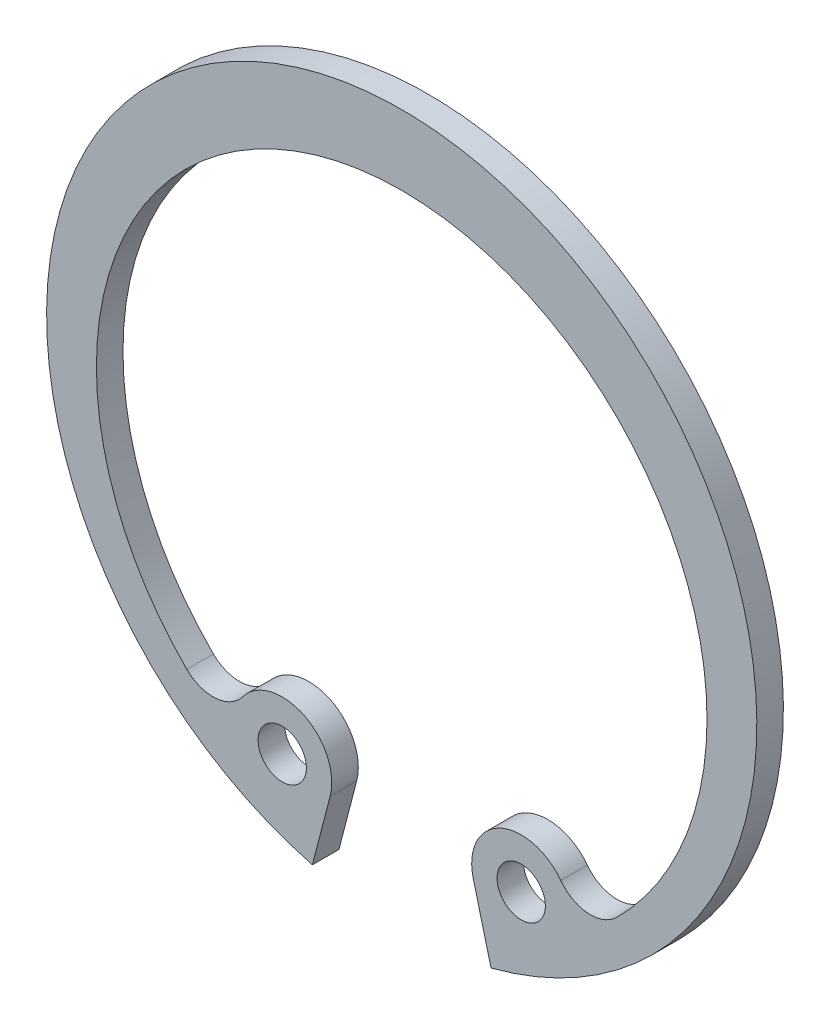
SolidWorks part; units mm, degrees
extrude "Body" add sketch "BodySke" against normal blind 1.1
sketch "BodySke" plane through (0, 0, 0) normal (0, 0, 1) x (1, 0, 0)
  line L0 (-1.5431, 0) -> (1.5431, 0) construction
  line L1 (0, 0) -> (0, 11.8) construction
  line L2 (3.6983, -14.2272) -> (2.9619, -11.3942)
  line L3 (-3.6983, -14.2272) -> (-2.9619, -11.3942)
  line L4 (0, 0) -> (9.8081, -10.9494) construction
  line L5 (0, 0) -> (-9.8081, -10.9494) construction
  line L6 (-4.6944, -9.9106) -> (-5.1975, -11.8463) construction
  line L7 (4.7571, -10.152) -> (5.1348, -11.6049) construction
  arc A0 (-2.9619, -11.3942) -> (-6.5847, -9.6467) centre (-4.946, -10.8784) ccw
  arc A1 (6.5847, -9.6467) -> (2.9619, -11.3942) centre (4.946, -10.8784) ccw
  arc A2 (8.8407, -9.8694) -> (-8.8407, -9.8694) centre (0, -0.8381) ccw construction
  arc A3 (3.6983, -14.2272) -> (-3.6983, -14.2272) centre (0, 0) ccw
  circle A4 centre (4.946, -10.8784) radius 1
  circle A5 centre (-4.946, -10.8784) radius 1
  circle A6 centre (4.946, -10.8784) radius 2.05 construction
  arc A7 (8.8959, -9.815) -> (-8.8959, -9.815) centre (0, -0.8381) ccw
  arc A8 (-4.946, -10.8784) -> (4.946, -10.8784) centre (0, 0) ccw construction
  arc A9 (-8.8959, -9.815) -> (-6.5847, -9.6467) centre (-7.8137, -8.7229) ccw
  arc A10 (6.5847, -9.6467) -> (8.8959, -9.815) centre (7.8137, -8.7229) ccw
  dimension "HoleDia" = 2
  dimension "HoleOffsetRad" = 11.95
  dimension "GrooveDia" = 29.4
  dimension "TipRad" = 2.05
  dimension "FilletRad" = 1.5375
  dimension "LargeRad" = 11.8
  dimension "SmallRad" = 13.25
  dimension "SmallAngle" = 83.706
  dimension "GapAngle" = 29.143
ref_plane "Plane1" through (0, 0, 0) normal (0, 0, 1) x (1, 0, 0)
ref_plane "Plane2" through (0, 0, 0) normal (0, 1, 0) x (1, 0, 0)
ref_plane "Plane3" through (0, 0, 0) normal (1, 0, 0) x (0, 0, -1)
sketch "Clipboard" plane through (0, 0, 0) normal (0, 0, 1) x (1, 0, 0)
  line L0 (0, 0) -> (2.9, 0)
  line L1 (0, 0) -> (0, 1.45)
  line L2 (0, 0) -> (0, -4.8)
  circle A0 centre (0, 0) radius 1
  circle A1 centre (0, 0) radius 14
  dimension "HoleDia" = 2
  dimension "BoreDia" = 28
  dimension "LargeSection" = 2.9
  dimension "SmallSection" = 1.45
  dimension "LugSection" = 4.8
sketch "ModLugSke" plane through (0, 0, 0) normal (0, 0, 1) x (1, 0, 0)
  line L0 (3.6983, -14.2272) -> (2.5157, -9.6779)
  line L1 (-3.6983, -14.2272) -> (-2.5157, -9.6779)
  line L2 (7.9458, -5.9054) -> (11.7983, -8.7687) construction
  line L3 (-7.9458, -5.9054) -> (-11.7983, -8.7687) construction
  line L4 (-3.6983, -14.2272) -> (-2.9619, -11.3942) construction
  line L5 (2.9619, -11.3942) -> (3.6983, -14.2272) construction
  line L6 (0, 0) -> (0, -18.0732) construction
  line L7 (10.5254, -7.8226) -> (11.7983, -8.7687)
  line L8 (-11.7983, -8.7687) -> (-10.5254, -7.8226)
  arc A0 (3.6983, -14.2272) -> (11.7983, -8.7687) centre (0, 0) ccw
  arc A1 (-5.5669, -8.1866) -> (-2.5864, -9.5562) centre (0, 0) ccw
  arc A2 (3.6983, -14.2272) -> (-3.6983, -14.2272) centre (0, 0) ccw construction
  arc A3 (6.5847, -9.6467) -> (2.9619, -11.3942) centre (4.946, -10.8784) ccw construction
  arc A4 (-5.5669, -8.1866) -> (-5.6932, -8.1979) centre (-5.6231, -8.2693) ccw
  arc A5 (-10.5254, -7.8226) -> (-5.6932, -8.1979) centre (-7.9458, -5.9054) ccw
  arc A6 (8.8959, -9.815) -> (-8.8959, -9.815) centre (0, -0.8381) ccw construction
  arc A7 (5.6932, -8.1979) -> (10.5254, -7.8226) centre (7.9458, -5.9054) ccw
  arc A8 (2.5864, -9.5562) -> (5.5669, -8.1866) centre (0, 0) ccw
  arc A9 (-11.7983, -8.7687) -> (-3.6983, -14.2272) centre (0, 0) ccw
  circle A10 centre (-4.946, -10.8784) radius 1
  circle A11 centre (-4.946, -10.8784) radius 1 construction
  circle A12 centre (4.946, -10.8784) radius 1
  circle A13 centre (4.946, -10.8784) radius 1 construction
  arc A14 (-2.5864, -9.5562) -> (-2.5157, -9.6779) centre (-2.6125, -9.6527) cw
  arc A15 (2.5864, -9.5562) -> (2.5157, -9.6779) centre (2.6125, -9.6527) ccw
  arc A16 (5.5669, -8.1866) -> (5.6932, -8.1979) centre (5.6231, -8.2693) cw
  point P43 (2.4907, -9.5816)
  dimension "D1" = 0.1
extrude "ModLug" [suppressed] add sketch "ModLugSke" against normal through all
sketch "UnlSke" [suppressed] plane through (0, 0, 0) normal (0, 0, 1) x (1, 0, 0)
  line L0 (2.1178, -8.3352) -> (3.2259, -12.6966)
  line L1 (-2.1178, -8.3352) -> (-3.2259, -12.6966)
  line L2 (-3.2259, -12.6966) -> (-2.1422, -8.4315) construction
  line L3 (2.1422, -8.4315) -> (3.2259, -12.6966) construction
  arc A0 (2.1178, -8.3352) -> (-2.1178, -8.3352) centre (0, 0) ccw
  arc A1 (3.2259, -12.6966) -> (-3.2259, -12.6966) centre (0, 0) ccw
  arc A2 (3.2259, -12.6966) -> (-3.2259, -12.6966) centre (0, 0) ccw construction
  circle A4 centre (-4.4431, -9.5688) radius 1
  circle A5 centre (4.4431, -9.5688) radius 1
  circle A6 centre (4.4431, -9.5688) radius 1 construction
  circle A7 centre (-4.4431, -9.5688) radius 1 construction
  arc A8 (2.2134, -8.3103) -> (4.9183, -7.0548) centre (0, 0) ccw construction
extrude "Unlug" [suppressed] add sketch "UnlSke" against normal through all
equation "' \"BoreDia@Clipboard\" = 8"
equation "' \"Thickness@Body\" = 0.8"
equation "' \"GrooveDia@BodySke\" = 8.4"
equation "' \"LugSection@Clipboard\" = 2.4"
equation "' \"LargeSection@Clipboard\" = 1.1"
equation "' \"HoleDia@Clipboard\" = 1"
equation "' \"BoreDia@Clipboard\" = 25"
equation "' \"Thickness@Body\" = 1.2"
equation "' \"GrooveDia@BodySke\" = 26.2"
equation "' \"LugSection@Clipboard\" = 4.5"
equation "' \"LargeSection@Clipboard\" = 2.7"
equation "' \"HoleDia@Clipboard\" = 2"
equation "\"SmallSection@Clipboard\" = \"LargeSection@Clipboard\" * 0.5"
equation "\"TipRad@BodySke\" = (\"LugSection@Clipboard\" - (\"GrooveDia@BodySke\" / 2  -  \"BoreDia@Clipboard\" / 2 ) ) / 2"
equation "\"HoleOffsetRad@BodySke\" = (\"GrooveDia@BodySke\" / 2) - \"LugSection@Clipboard\"  + \"TipRad@BodySke\""
equation "\"LargeRad@BodySke\" =  \"GrooveDia@BodySke\" / 2 -  \"LargeSection@Clipboard\""
equation "\"SmallRad@BodySke\" =  \"GrooveDia@BodySke\" / 2 -  \"SmallSection@Clipboard\""
equation "\"HoleDia@BodySke\" =  \"HoleDia@Clipboard\""
equation "\"FilletRad@BodySke\" = \"TipRad@BodySke\" * 0.75"
equation "\"GapAngle@BodySke\" = 360 - 0.965 * 360 * ( \"BoreDia@Clipboard\" /  \"GrooveDia@BodySke\")"
equation "\"LugAng@ModLugSke\" = \"GapAngle@BodySke\"  + 2 * 360 * (\"LugSection@Clipboard\" / (\"BoreDia@Clipboard\" * 3.1416))"
